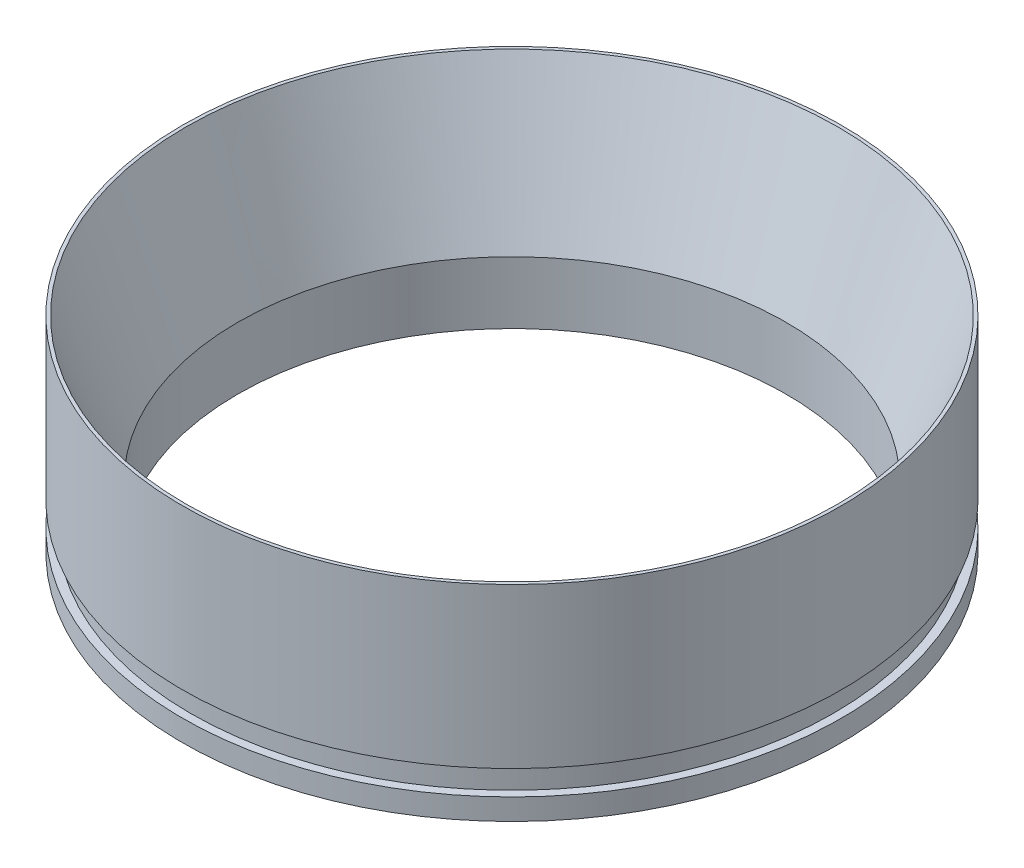
SolidWorks part; units mm, degrees
ref_plane "Front Plane" through (0, 0, 0) normal (0, 0, 1) x (1, 0, 0)
ref_plane "Top Plane" through (0, 0, 0) normal (0, 1, 0) x (1, 0, 0)
ref_plane "Right Plane" through (0, 0, 0) normal (1, 0, 0) x (0, 0, -1)
sketch "Sketch1" plane through (0, 0, 0) normal (0, 0, 1) x (1, 0, 0)
  line L0 (0, 0) -> (42.545, 0) construction
  line L3 (42.545, 9.652) -> (50.6222, 31.8439)
  line L4 (51.1302, 31.8439) -> (51.1302, 7.112)
  line L6 (51.1302, 0) -> (42.545, 0)
  line L7 (0, 33.2396) -> (0, 0) construction
  line L8 (0, 33.2396) -> (51.1302, 33.2396) construction
  line L9 (42.545, 9.652) -> (42.545, 33.2396) construction
  line L10 (50.6222, 31.8439) -> (51.1302, 31.8439)
  line L11 (50.6222, 31.8439) -> (51.1302, 33.2396) construction
  line L12 (51.1302, 33.2396) -> (51.1302, 31.8439) construction
  line L13 (42.545, 9.652) -> (42.545, 0)
  line L14 (51.1302, 7.112) -> (49.8602, 7.112)
  line L15 (49.8602, 7.112) -> (49.8602, 3.302)
  line L16 (49.8602, 3.302) -> (51.1302, 3.302)
  line L17 (51.1302, 3.302) -> (51.1302, 0)
  line L19 (42.545, 9.652) -> (42.545, 7.112) construction
  line L20 (42.545, 7.112) -> (49.8602, 7.112) construction
  point P11 (45.085, 9.5135)
  point P12 (0, 0)
  dimension "D2" = 42.545
  dimension "D3" = 20
  dimension "D4" = 51.1302
  dimension "D5" = 0.508
  dimension "D6" = 9.652
  dimension "D7" = 2.54
  dimension "D8" = 3.81
  dimension "D9" = 1.27
revolve "Revolve1" add sketch "Sketch1" angle 360 about L7
